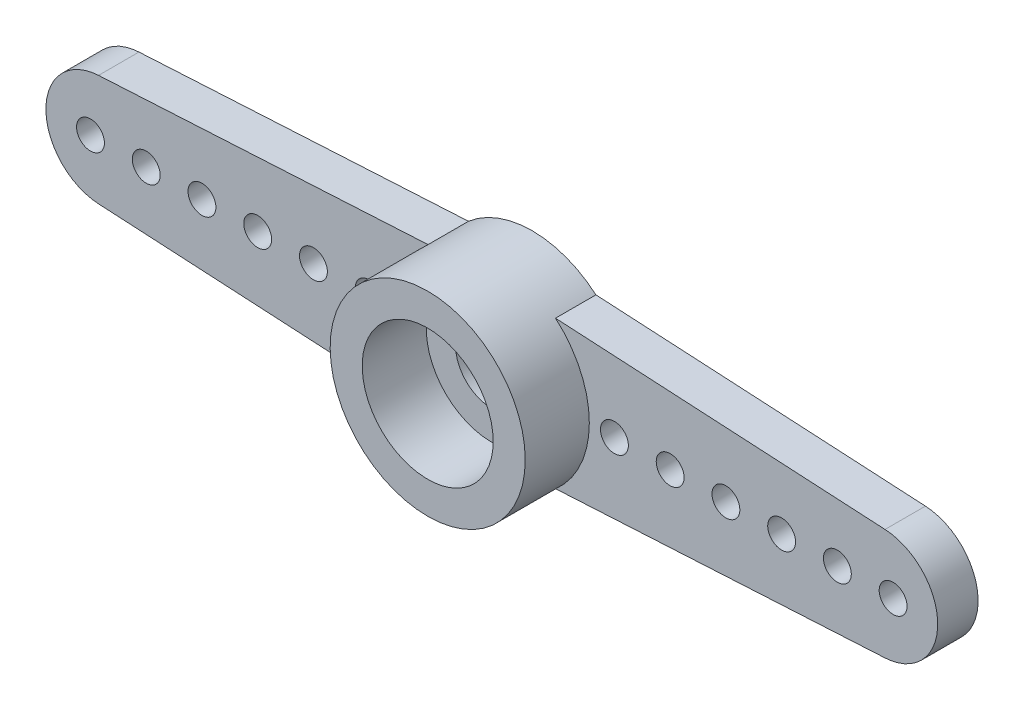
SolidWorks part; units mm, degrees
material "ABS"
ref_plane "前视基准面" through (0, 0, 0) normal (0, 0, 1) x (1, 0, 0)
ref_plane "上视基准面" through (0, 0, 0) normal (0, 1, 0) x (1, 0, 0)
ref_plane "右视基准面" through (0, 0, 0) normal (1, 0, 0) x (0, 0, -1)
other "Configuration Table"
sketch "草图1" plane through (0, 0, 0) normal (0, 0, 1) x (1, 0, 0)
  line L0 (-4.7548, 3.0389) -> (16.9402, 1.8407)
  line L1 (-3.5, 8.2939) -> (-3.5, -8.5966) construction
  line L2 (16.3041, -1.8758) -> (-5.4983, -3.08)
  line L3 (16, 7.2301) -> (16, -7.2734) construction
  line L4 (2.2864, 6.2453) -> (2.2864, -4.4515) construction
  circle A0 centre (14, 0) radius 2
  circle A1 centre (0, 0) radius 2.7721
  circle A2 centre (0, 0) radius 3.5
  point P14 (2.2864, -2.65)
  point P15 (2.2864, 2.65)
  dimension "D2" = 7
  dimension "D3" = 4
  dimension "D1" = 19.5
  dimension "D4" = 5.3
extrude "凸台-拉伸1" add sketch "草图1" along normal blind 1.45 contours L2 A2 L0 A1 | A1 | L0 A2 L2 A1 | L0 A2 | L2 A2 | A2 L2 A0 L0 | A0 A2
sketch "草图2" plane through (0, 0, 1.45) normal (0, 0, 1) x (1, 0, 0)
  circle A1 centre (0, 0) radius 2.35
  circle A2 centre (0, 0) radius 3.5
  arc A3 (2.2864, 2.65) -> (2.2864, -2.65) centre (0, 0) ccw construction
  dimension "D1" = 4.7
extrude "凸台-拉伸2" add sketch "草图2" along normal blind 2.3
sketch "草图3" plane through (0, 0, 0) normal (0, 0, -1) x (-1, 0, 0)
  circle A0 centre (0, 0) radius 2.3
  dimension "D1" = 4.6
extrude "切除-拉伸1" cut sketch "草图3" against normal blind 0.7
sketch "草图4" plane through (0, 0, 0.7) normal (0, 0, -1) x (-1, 0, 0)
  circle A0 centre (0, 0) radius 1.3
  dimension "D1" = 2.6
extrude "切除-拉伸2" cut sketch "草图4" against normal through all
sketch "草图5" plane through (0, 0, 0) normal (0, 0, -1) x (-1, 0, 0)
  line L0 (-16, 4.7285) -> (-16, -4.2754) construction
  line L1 (-14.9, 4.1484) -> (-14.9, -4.5312) construction
  arc A1 (-14.1103, 1.997) -> (-14.1103, -1.997) centre (-14, 0) ccw construction
  circle A2 centre (-14.4, 0) radius 0.5
  dimension "D1" = 1
  dimension "D2" = 1.1
extrude "切除-拉伸3" cut sketch "草图5" against normal through all contours A2
pattern_linear "阵列(线性)1" count 6 spacing 2 along (-1, 0, 0) of "切除-拉伸3"
mirror "镜向1" about plane through (0, 0, 0) normal (1, 0, 0) of "凸台-拉伸1", "切除-拉伸1", "切除-拉伸2", "切除-拉伸3", "阵列(线性)1"
